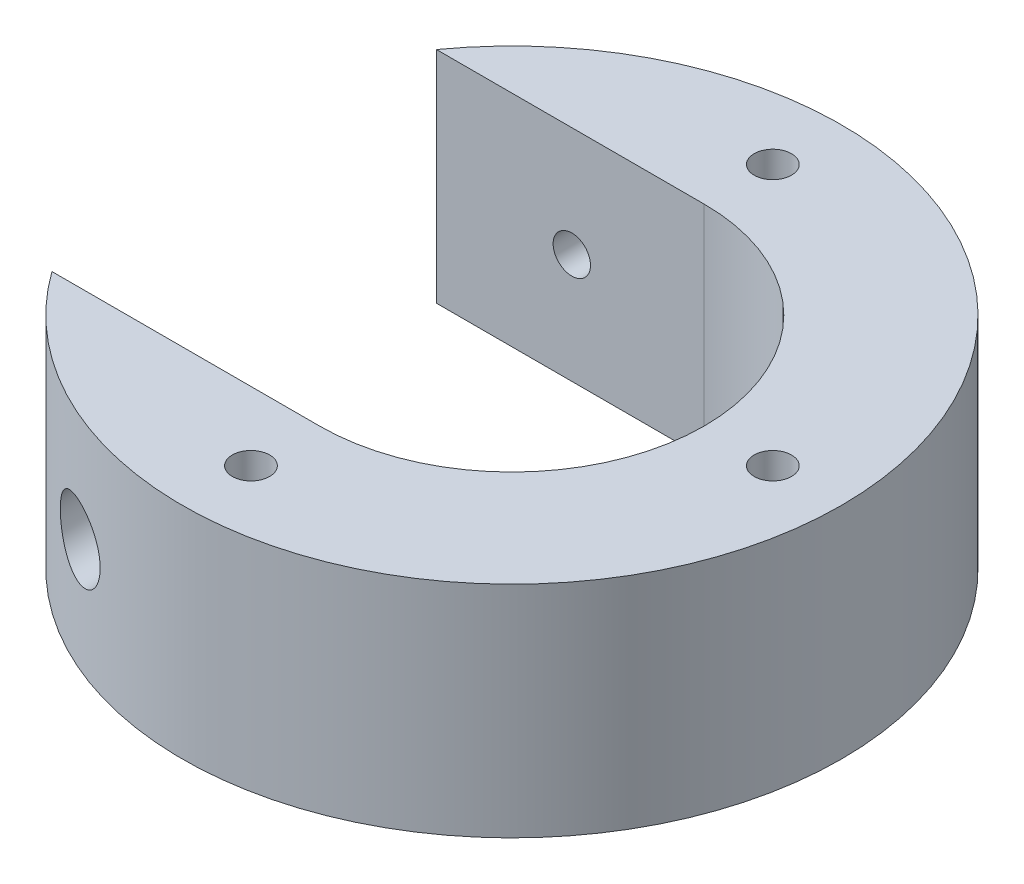
SolidWorks part; units mm, degrees
ref_plane "Front Plane" through (0, 0, 0) normal (0, 0, 1) x (1, 0, 0)
ref_plane "Top Plane" through (0, 0, 0) normal (0, 1, 0) x (1, 0, 0)
ref_plane "Right Plane" through (0, 0, 0) normal (1, 0, 0) x (0, 0, -1)
sketch "Sketch2" plane through (0, 0, 0) normal (0, 1, 0) x (1, 0, 0)
  circle A0 centre (0, 0) radius 30
  dimension "D1" = 60
extrude "Boss-Extrude1" add sketch "Sketch2" along normal blind 20
sketch "Sketch3" plane through (0, 20, 0) normal (0, 1, 0) x (1, 0, 0)
  line L0 (-24.367, 17.5) -> (-19.1, 17.5)
  line L1 (-19.1, 17.5) -> (-19.1, 21.5)
  line L2 (-19.1, 21.5) -> (0, 21.5)
  line L3 (0, 21.5) -> (0, 17.5)
  line L4 (0, -21.5) -> (0, -17.5)
  line L5 (0, -21.5) -> (-19.1, -21.5)
  line L6 (-19.1, -21.5) -> (-19.1, -17.5)
  line L7 (-19.1, -17.5) -> (-24.367, -17.5)
  line L9 (-13.1, 13.5) -> (-23.1, 13.5)
  line L10 (-23.1, 13.5) -> (-23.1, 8.5)
  line L11 (-23.1, 8.5) -> (-11.1, 8.5)
  line L12 (-11.1, 8.5) -> (-11.1, 2.5)
  line L13 (-11.1, 2.5) -> (-23.1, 2.5)
  line L14 (-23.1, 2.5) -> (-23.1, -2.5)
  line L15 (-23.1, -2.5) -> (-11.1, -2.5)
  line L16 (-11.1, -2.5) -> (-11.1, -8.5)
  line L17 (-11.1, -8.5) -> (-23.1, -8.5)
  line L18 (-23.1, -8.5) -> (-23.1, -13.5)
  line L22 (-23.1, -13.5) -> (-11.1, -13.5)
  line L23 (-2, 6.8125) -> (-2, 9.0619)
  line L25 (-2, -6.8125) -> (-2, -9.0619)
  line L28 (-2, -9.0619) -> (-2, -17.5)
  line L29 (-2, 9.0619) -> (-2, 17.5)
  line L30 (0, 17.5) -> (0, -17.5) construction
  line L31 (-2, 17.5) -> (0, 17.5)
  line L32 (-2, -17.5) -> (0, -17.5)
  circle A0 centre (0, 0) radius 30 construction
  arc A1 (0, 17.5) -> (0, -17.5) centre (0, 0) cw
  arc A2 (-24.367, 17.5) -> (-24.367, -17.5) centre (0, 0) ccw
  arc A4 (0, 5.1) -> (0, -5.1) centre (0, 0) ccw construction
  arc A5 (-13.1, 13.5) -> (-2, 9.0619) centre (-13.1, -2.6) cw
  arc A6 (-2, 6.8125) -> (-2, -6.8125) centre (0, 0) ccw
  arc A7 (-11.1, -13.5) -> (-2, -9.0619) centre (-11.1, -1.9515) ccw
  point P35 (-23.1, 0)
  point P36 (-7.1, 0)
  dimension "D9" = 13.1
  dimension "D7" = 2
  dimension "D12" = 5.1
  dimension "D10" = 16.1
  dimension "D2" = 4
  dimension "D3" = 35
  dimension "D4" = 4
  dimension "D5" = 5
  dimension "D6" = 5
  dimension "D8" = 19.1
  dimension "D11" = 12
  dimension "D13" = 2
  dimension "D14" = 4
extrude "Cut-Extrude2" cut sketch "Sketch3" against normal through all
hole_wizard "M3 Clearance Hole1" positions "Sketch4" profile "Sketch5" hole size "M3" standard "ANSI Metric" end condition through all
sketch "Sketch4" plane through (0, 0, 0) normal (0, -1, 0) x (-1, 0, 0)
  line L9 (0, 30) -> (0, 17.5) construction
  line L11 (0, -30) -> (0, -17.5) construction
  line L13 (-30, 0) -> (-17.5, 0) construction
  circle A3 centre (0, 0) radius 30 construction
  arc A4 (0, 17.5) -> (0, -17.5) centre (0, 0) ccw construction
  point P0 (0, 23.75)
  point P2 (-23.75, 0)
  point P4 (0, -23.75)
  point P76 (0, 23.75)
  point P77 (-23.75, 0)
  point P78 (0, -23.75)
sketch "Sketch5" plane through (0, 0, -23.75) normal (1, 0, 0) x (0, 0, -1)
  line L0 (0, 0) -> (0, 20)
  line L1 (0, 20) -> (1.7, 20)
  line L2 (1.7, 20) -> (1.7, 0.025)
  line L3 (1.7, 0.025) -> (1.725, 0)
  line L5 (1.725, 0) -> (0, 0)
  line L6 (-1.7, 0.025) -> (-1.725, 0) construction
  line L11 (0, -6.35) -> (0, 107.95) construction
  dimension "Thru Hole Dia." = 3.4
  dimension "Thru Hole Depth" = 20
  dimension "Near C'Sink Dia." = 3.45
  dimension "Near C'Sink Angle" = 90
sketch "Sketch6" plane through (0, 20, 0) normal (0, 1, 0) x (1, 0, 0)
  line L1 (-24.367, 17.5) -> (-2, 17.5)
  line L2 (-2, 17.5) -> (-2, -17.5)
  line L3 (-2, -17.5) -> (-24.367, -17.5)
  line L4 (-2, 6.8125) -> (-2, 17.5) construction
  arc A0 (-24.367, 17.5) -> (-24.367, -17.5) centre (0, 0) ccw
  circle A1 centre (0, 0) radius 30 construction
  point P3 (-2, 0)
extrude "Cut-Extrude3" cut sketch "Sketch6" against normal through all
ref_plane "Plane2" through (0, 0, 30) normal (0, 0, 1) x (1, 0, 0)
hole_wizard "CBORE for M3 SHCS1" positions "Sketch7" profile "Sketch8" counterbore size "M3" standard "ANSI Metric" end condition up to next
sketch "Sketch7" plane through (0, 0, 30) normal (0, 0, 1) x (1, 0, 0)
  line L2 (-24.367, 0) -> (-24.367, 20) construction
  point P2 (-12.047, 10)
  point P12 (-24.367, 10)
  dimension "D1" = 12.32
sketch "Sketch8" plane through (-12.047, 10, 30) normal (1, 0, 0) x (0, -1, 0)
  line L0 (0, 0) -> (0, 12.5)
  line L1 (0, 12.5) -> (1.7, 12.5)
  line L3 (1.7, 12.5) -> (1.7, 7)
  line L4 (3.25, 7) -> (1.7, 7)
  line L5 (3.25, 7) -> (3.25, 0.025)
  line L6 (3.25, 0.025) -> (3.275, 0)
  line L7 (3.275, 0) -> (0, 0)
  line L8 (-3.25, 0.025) -> (-3.275, 0) construction
  line L11 (0, -6.35) -> (0, 107.95) construction
  dimension "Thru Hole Dia." = 3.4
  dimension "Thru Hole Depth" = 12.5
  dimension "C'Bore Dia." = 6.5
  dimension "C'Bore Depth" = 7
  dimension "Near C'Sink Dia." = 6.55
  dimension "Near C'Sink Angle" = 90
mirror "Mirror1" about plane through (0, 0, 0) normal (0, 0, 1) of "CBORE for M3 SHCS1"
